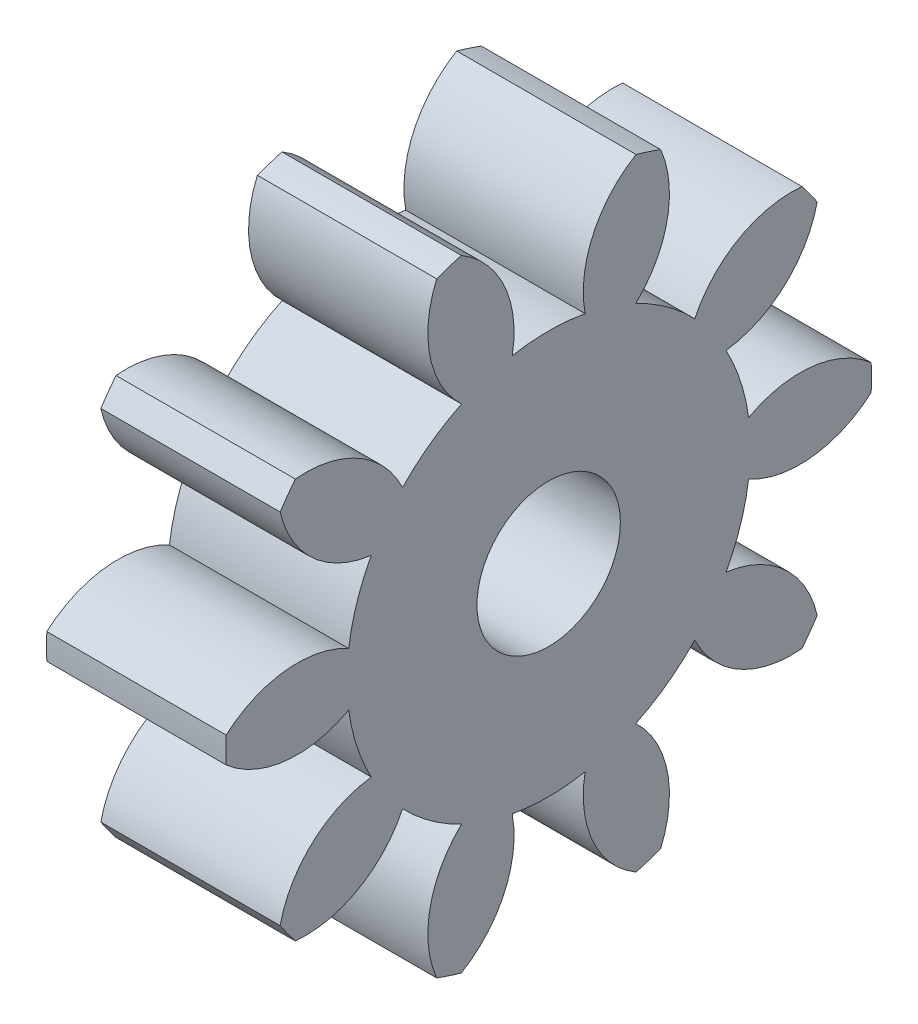
SolidWorks part; units mm, degrees
ref_plane "Plane1" through (0, 0, 0) normal (0, 0, 1) x (1, 0, 0)
ref_plane "Plane2" through (0, 0, 0) normal (0, 1, 0) x (1, 0, 0)
ref_plane "Plane3" through (0, 0, 0) normal (1, 0, 0) x (0, 0, -1)
sketch "HoldingSke" plane through (0, 0, 0) normal (0, 1, 0) x (1, 0, 0)
  line L0 (0, 0) -> (0.6565, -0.1158)
  line L1 (-15, 0) -> (100, 0) construction
  line L2 (0, 0) -> (-2.1039, 2.3779)
  line L3 (0, 0) -> (-11.863, 4.5341)
  line L4 (0, 0) -> (8.5048, 1.4996)
  line L5 (0, 0) -> (-46.8476, -17.4728)
  line L6 (0, 0) -> (-4.1448, -2.7965)
  line L7 (-2.1039, 2.3779) -> (8.6586, 51.2059)
  line L8 (-76.2, 54.61) -> (-75.9, 54.61)
  line L9 (-67.7845, 28.3722) -> (-49.3413, 33.142)
  line L10 (-76.2, 71.12) -> (104.1128, 71.12)
  line L11 (0, 0) -> (-5, 0)
  line L12 (-76.2, 101.6) -> (-76.147, 101.6)
  line L13 (24.9733, 27.94) -> (52.9518, 28.4284)
  line L14 (24.9733, 27.94) -> (24.9743, 27.94)
  line L15 (24.9733, 27.94) -> (100.4006, 29.5858)
  line L16 (-63.627, -1.5) -> (-12.827, -1.5)
  circle A0 centre (0, 0) radius 1
  circle A1 centre (0, 0) radius 5.624
  circle A2 centre (0, 0) radius 37.5
  circle A3 centre (0, 0) radius 1
  dimension "MHD" = 11.248
  dimension "Hub_dia" = 75
  dimension "Bore" = 2
  dimension "MBD" = 2
  dimension "Num_teeth" = 10
  dimension "Pitch" = 0.6667
  dimension "Overall_len" = 50
  dimension "Show_teeth" = 10
  dimension "Thickness" = 5
  dimension "OAL" = 50.0001
  dimension "T_dim" = 0.3
  dimension "Ap" = 14.5
  dimension "H" = 19.05
  dimension "Pitch_radius" = 180.3128
  dimension "Width" = 5
  dimension "Backlash" = 0.053
  dimension "Addendum_fac" = 1
  dimension "Dedendum_fac" = 1.25
  dimension "Clearance_fac" = 0.25
  dimension "Dedendum_add" = 0.001
  dimension "Module" = 1.5
sketch "BasProSke" plane through (0, 0, 0) normal (0, 1, 0) x (1, 0, 0)
  line L0 (-10, 0) -> (60, 0) construction
  line L1 (0, 0) -> (0, 9)
  line L2 (0, 0) -> (5, 0)
  line L3 (5, 0) -> (5, 9)
  line L4 (5, 9) -> (0, 9)
  dimension "Thickness" = 5
  dimension "Diameter" = 18
revolve "Base-Revolve" add sketch "BasProSke" angle 360 about L0
sketch "TooCutSke" plane through (0, 0, 0) normal (1, 0, 0) x (0, 0, -1)
  line L1 (0, 0) -> (0, 107) construction
  line L2 (0, 0) -> (-1.2658, 7.3924) construction
  line L3 (0, 0) -> (-4.5869, 14.117) construction
  line L4 (-1.2658, 7.3924) -> (-2.2934, 7.0585) construction
  arc A0 (1.0161, 5.5314) -> (-1.0161, 5.5314) centre (0, 0) ccw
  arc A1 (2.4664, 8.6819) -> (-2.4664, 8.6819) centre (0, 0) ccw
  circle A2 centre (0, 0) radius 7.5 construction
  circle A3 centre (0, 0) radius 7.2611 construction
  arc A4 (-1.0161, 5.5314) -> (-2.4664, 8.6819) centre (-3.965, 6.083) ccw
  arc A5 (2.4664, 8.6819) -> (1.0161, 5.5314) centre (3.965, 6.083) ccw
  dimension "Root_dia" = 11.248
  dimension "Overcut_dia" = 18.0508
  dimension "Pitch_dia" = 15
  dimension "Base_dia" = 14.5222
  dimension "Flank_rad" = 3
  dimension "Half_ang" = 18
  dimension "Half_CT" = 1.0805
extrude "ToothCut" cut sketch "TooCutSke" along normal through all
fillet "Breaks" [suppressed] radius 0.03
fillet "RootFillets" [suppressed] radius 0.376
pattern_circular "TeethCuts" count 10 every 36 about axis through (-10, 0, 0) along (1, 0, 0) of "ToothCut", "RootFillets", "Breaks"
sketch "HubNeaOneSke" plane through (0, 0, 0) normal (-1, 0, 0) x (0, 0, 1)
  circle A0 centre (0, 0) radius 5.624
  dimension "Diameter" = 11.248
extrude "HubNearOne" [suppressed] add sketch "HubNeaOneSke" along normal blind 45.0001
sketch "HubNeaBotSke" plane through (0, 0, 0) normal (-1, 0, 0) x (0, 0, 1)
  circle A0 centre (0, 0) radius 5.624
  dimension "Diameter" = 11.248
extrude "HubNearBoth" [suppressed] add sketch "HubNeaBotSke" along normal blind 22.5
ref_plane "FarPln" through (5, 0, 0) normal (1, 0, 0) x (0, 0, -1)
sketch "HubFarSke" plane through (5, 0, 0) normal (1, 0, 0) x (0, 0, -1)
  circle A0 centre (0, 0) radius 5.624
  dimension "Diameter" = 11.248
extrude "HubFar" [suppressed] add sketch "HubFarSke" along normal blind 22.5
sketch "BorSke" plane through (0, 0, 0) normal (1, 0, 0) x (0, 0, -1)
  circle A0 centre (0, 0) radius 1
  dimension "Diameter" = 2
extrude "Bore" cut sketch "BorSke" along normal mid plane 100.0001
sketch "KeySke" plane through (0, 0, 0) normal (1, 0, 0) x (0, 0, -1)
  line L0 (-0.4, 0) -> (-0.4, 1.3)
  line L1 (-0.4, 1.3) -> (0.4, 1.3)
  line L2 (0.4, 1.3) -> (0.4, 0)
  line L3 (0, 0) -> (0, 34) construction
  line L4 (-0.4, 0) -> (0.4, 0)
  dimension "Offset" = 1.3
  dimension "Width" = 0.8
extrude "Keyway" [suppressed] cut sketch "KeySke" along normal mid plane 100.0001
pattern_circular "Keyway2" [suppressed] count 2 every 90 about axis through (-10, 0, 0) along (1, 0, 0)
sketch "Sketch1" plane through (5, 0, 0) normal (1, 0, 0) x (0, 0, -1)
  circle A0 centre (0, 0) radius 2
extrude "Cut-Extrude1" cut sketch "Sketch1" against normal through all
equation "' \"Module@HoldingSke\" = 6.35"
equation "' \"Num_teeth@HoldingSke\" = 12"
equation "' \"Ap@HoldingSke\" =  20"
equation "' \"Ap@HoldingSke\" = 20"
equation "' \"Width@HoldingSke\" = 0.5 * 25.4"
equation "' \"Hub_dia@HoldingSke\"= 1 * 25.4"
equation "' \"Hub_dia@HoldingSke\" = 1 * 25.4"
equation "' \"Overall_len@HoldingSke\" = 1.0 * 25.4"
equation "' \"Bore@HoldingSke\" = 0.75 * 25.4"
equation "' \"T_dim@HoldingSke\" = 0.1 * 25.4"
equation "' \"Width@KeySke\" = 0.25 * 25.4"
equation "' \"Show_teeth@HoldingSke\" = 13"
equation "' \"Backlash@HoldingSke\" = 0.009 * 25.4"
equation "' \"Addendum_fac@HoldingSke\" = 1.0"
equation "' \"Dedendum_fac@HoldingSke\" = 1.25"
equation "' \"Dedendum_add@HoldingSke\" = 0.00005 * 25.4"
equation "' \"Clearance_fac@HoldingSke\" = 0.25"
equation "\"Pitch@HoldingSke\" = 1 / \"Module@HoldingSke\""
equation "\"Overcut_dia@TooCutSke\" = (\"Num_teeth@HoldingSke\" + 2 * \"Addendum_fac@HoldingSke\") / \"Pitch@HoldingSke\" + 0.002 * 25.4"
equation "\"Pitch_dia@TooCutSke\" = \"Num_teeth@HoldingSke\" / \"Pitch@HoldingSke\""
equation "\"Base_dia@TooCutSke\" = \"Num_teeth@HoldingSke\" / \"Pitch@HoldingSke\" * cos((\"Ap@HoldingSke\"  * 3.14159265 / 180))"
equation "\"Root_dia@TooCutSke\" = (\"Num_teeth@HoldingSke\" + 2) / \"Pitch@HoldingSke\" - 2 * (\"Addendum_fac@HoldingSke\" + \"Dedendum_fac@HoldingSke\") / \"Pitch@HoldingSke\" - \"Dedendum_add@HoldingSke\" * 2"
equation "\"Half_ang@TooCutSke\" = 180 / \"Num_teeth@HoldingSke\""
equation "\"Half_CT@TooCutSke\" = \"Num_teeth@HoldingSke\" / \"Pitch@HoldingSke\" * sin((3.14159265 / 2 / \"Num_teeth@HoldingSke\")) / 2 - 7 * \"Backlash@HoldingSke\" / 4"
equation "\"Flank_rad@TooCutSke\" = \"Num_teeth@HoldingSke\" / \"Pitch@HoldingSke\" / 5"
equation "\"Radius@RootFillets\" = \"Clearance_fac@HoldingSke\" / \"Pitch@HoldingSke\" + \"Dedendum_add@HoldingSke\""
equation "\"Break_rad@Breaks\" = 0.02 / \"Pitch@HoldingSke\""
equation "\"Thickness@HoldingSke\" = \"Width@HoldingSke\""
equation "\"OAL@HoldingSke\" = \"Thickness@HoldingSke\""
equation "\"MHD@HoldingSke\" = (\"Num_teeth@HoldingSke\" + 2) / \"Pitch@HoldingSke\" - 2 * (\"Addendum_fac@HoldingSke\" + \"Dedendum_fac@HoldingSke\")  / \"Pitch@HoldingSke\" - \"Dedendum_add@HoldingSke\" * 2"
equation "\"MBD@HoldingSke\" = (\"Num_teeth@HoldingSke\" + 2) / \"Pitch@HoldingSke\" - 2 * (\"Addendum_fac@HoldingSke\" + \"Dedendum_fac@HoldingSke\")  / \"Pitch@HoldingSke\" - \"Dedendum_add@HoldingSke\" * 2 - 0.002 * 25.4"
equation "\"MHD@HoldingSke\" = ((sgn( \"MHD@HoldingSke\" - \"Hub_dia@HoldingSke\" )-1)*( \"MHD@HoldingSke\" - \"Hub_dia@HoldingSke\" ))/-2+ \"Hub_dia@HoldingSke\""
equation "\"MBD@HoldingSke\" = ((sgn( \"MBD@HoldingSke\" - \"Bore@HoldingSke\" )-1)*( \"MBD@HoldingSke\" - \"Bore@HoldingSke\" ))/-2+ \"Bore@HoldingSke\""
equation "\"OAL@HoldingSke\" = ((sgn( \"OAL@HoldingSke\" - \"Overall_len@HoldingSke\" )+1)*( \"OAL@HoldingSke\" - \"Overall_len@HoldingSke\" ))/2 + \"Overall_len@HoldingSke\" + 0.000002 * 25.4"
equation "\"Num_teeth@TeethCuts\" = int( \"Show_teeth@HoldingSke\" ) + 1"
equation "\"Num_teeth@TeethCuts\" = ((sgn( \"Num_teeth@TeethCuts\" - \"Num_teeth@HoldingSke\" )-1)*( \"Num_teeth@TeethCuts\" - \"Num_teeth@HoldingSke\" ))/-2+ \"Num_teeth@HoldingSke\""
equation "\"Num_teeth@TeethCuts\" = ((sgn( \"Num_teeth@TeethCuts\" - 2.0)+1)*( \"Num_teeth@TeethCuts\" - 2.0))/2 +2.0"
equation "\"Angle@TeethCuts\" = 360.0 / \"Num_teeth@HoldingSke\""
equation "\"Diameter@BasProSke\" = (\"Num_teeth@HoldingSke\" + 2 * \"Addendum_fac@HoldingSke\") / \"Pitch@HoldingSke\""
equation "\"Thickness@BasProSke\"  = \"Thickness@HoldingSke\""
equation "' \"Fillet_rad@BasProSke\" =  \"Thickness@HoldingSke\" * 0.05"
equation "' \"Fillet_rad@BasProSke\" = \"Thickness@HoldingSke\" * 0.05"
equation "\"MHD@HoldingSke\" = ((sgn( \"MHD@HoldingSke\" - \"Root_dia@TooCutSke\" )-1)*( \"MHD@HoldingSke\" - \"Root_dia@TooCutSke\" ))/-2+ \"Root_dia@TooCutSke\""
equation "\"Diameter@HubNeaOneSke\" = \"MHD@HoldingSke\""
equation "\"Length@HubNearOne\" = \"OAL@HoldingSke\" - \"Thickness@BasProSke\""
equation "\"Diameter@HubNeaBotSke\" = \"MHD@HoldingSke\""
equation "\"Length@HubNearBoth\" = ( \"OAL@HoldingSke\" - \"Thickness@BasProSke\" ) / 2.0"
equation "\"Thickness@FarPln\" = \"Thickness@BasProSke\""
equation "\"Diameter@HubFarSke\" = \"MHD@HoldingSke\""
equation "\"Length@HubFar\" = ( \"OAL@HoldingSke\" - \"Thickness@BasProSke\" ) / 2.0"
equation "\"Diameter@BorSke\" = \"MBD@HoldingSke\""
equation "\"D1@Bore\" = \"OAL@HoldingSke\" * 2.0"
equation "\"D1@Keyway\" = \"OAL@HoldingSke\" * 2.0"
equation "\"Offset@KeySke\" = \"T_dim@HoldingSke\" + \"MBD@HoldingSke\" / 2.0"
